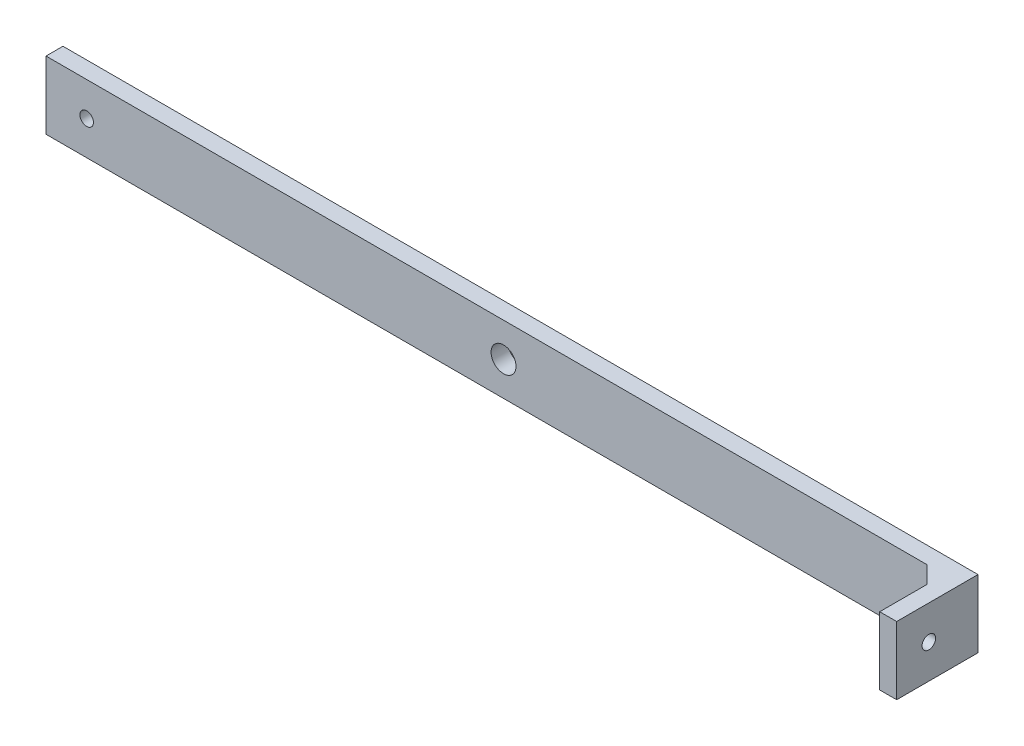
SolidWorks part; units mm, degrees
ref_plane "Front Plane" through (0, 0, 0) normal (0, 0, 1) x (1, 0, 0)
ref_plane "Top Plane" through (0, 0, 0) normal (0, 1, 0) x (1, 0, 0)
ref_plane "Right Plane" through (0, 0, 0) normal (1, 0, 0) x (0, 0, -1)
sketch "Sketch1" plane through (0, 0, 0) normal (0, 0, 1) x (1, 0, 0)
  line L1 (-135, -10) -> (135, -10)
  line L2 (-135, -10) -> (-135, 10)
  line L3 (-135, 10) -> (135, 10)
  line L4 (135, -10) -> (135, 10)
  line L5 (-135, -10) -> (135, 10) construction
  line L6 (-135, 10) -> (135, -10) construction
  point P0 (0, 0)
  dimension "D1" = 20
  dimension "D2" = 270
extrude "Boss-Extrude1" add sketch "Sketch1" along normal blind 5
sketch "Sketch2" plane through (0, 0, 5) normal (0, 0, 1) x (1, 0, 0)
  line L0 (-135, -10) -> (135, -10) construction
  line L1 (135, 10) -> (130, 10)
  line L2 (135, 10) -> (135, -10)
  line L3 (135, -10) -> (130, -10)
  line L4 (130, 10) -> (130, -10)
  dimension "D1" = 5
extrude "Boss-Extrude2" add sketch "Sketch2" along normal blind 19
sketch "Sketch3" plane through (135, 0, 0) normal (1, 0, 0) x (0, 0, -1)
  line L0 (-24, -10) -> (0, -10) construction
  line L1 (-24, -10) -> (-24, 10) construction
  circle A0 centre (-14.5, 0) radius 2
  dimension "D1" = 4
  dimension "D2" = 10
  dimension "D3" = 9.5
extrude "Cut-Extrude1" cut sketch "Sketch3" against normal through all
sketch "Sketch4" plane through (130, 0, 0) normal (-1, 0, 0) x (0, 0, 1)
  line L1 (5, -10) -> (10, -10)
  line L2 (5, -10) -> (5, -5)
  line L3 (5, -5) -> (10, -5)
  line L4 (10, -10) -> (10, -5)
  line L5 (5, 10) -> (10, 10)
  line L6 (5, 10) -> (5, 5)
  line L7 (5, 5) -> (10, 5)
  line L8 (10, 10) -> (10, 5)
  dimension "D1" = 5
  dimension "D2" = 5
  dimension "D3" = 5
  dimension "D4" = 5
extrude "Boss-Extrude3" add sketch "Sketch4" along normal blind 5
sketch "Sketch5" plane through (0, -10, 0) normal (0, -1, 0) x (1, 0, 0)
  line L0 (125, 5) -> (130, 10)
  line L1 (130, 10) -> (125, 10)
  line L2 (125, 10) -> (125, 5)
extrude "Cut-Extrude2" cut sketch "Sketch5" against normal through all
sketch "Sketch6" plane through (0, 0, 0) normal (0, 0, -1) x (-1, 0, 0)
  line L0 (-135, -10) -> (-135, 10) construction
  line L1 (135, -10) -> (-135, -10) construction
  circle A0 centre (123, 0) radius 2
  dimension "D1" = 4
  dimension "D2" = 258
  dimension "D3" = 10
extrude "Cut-Extrude3" cut sketch "Sketch6" against normal through all
sketch "Sketch7" plane through (0, 0, 0) normal (0, 0, -1) x (-1, 0, 0)
  line L0 (-135, -10) -> (-135, 10) construction
  circle A0 centre (0, 0) radius 3.6829
  dimension "D1" = 135
extrude "Cut-Extrude4" cut sketch "Sketch7" against normal blind 10
